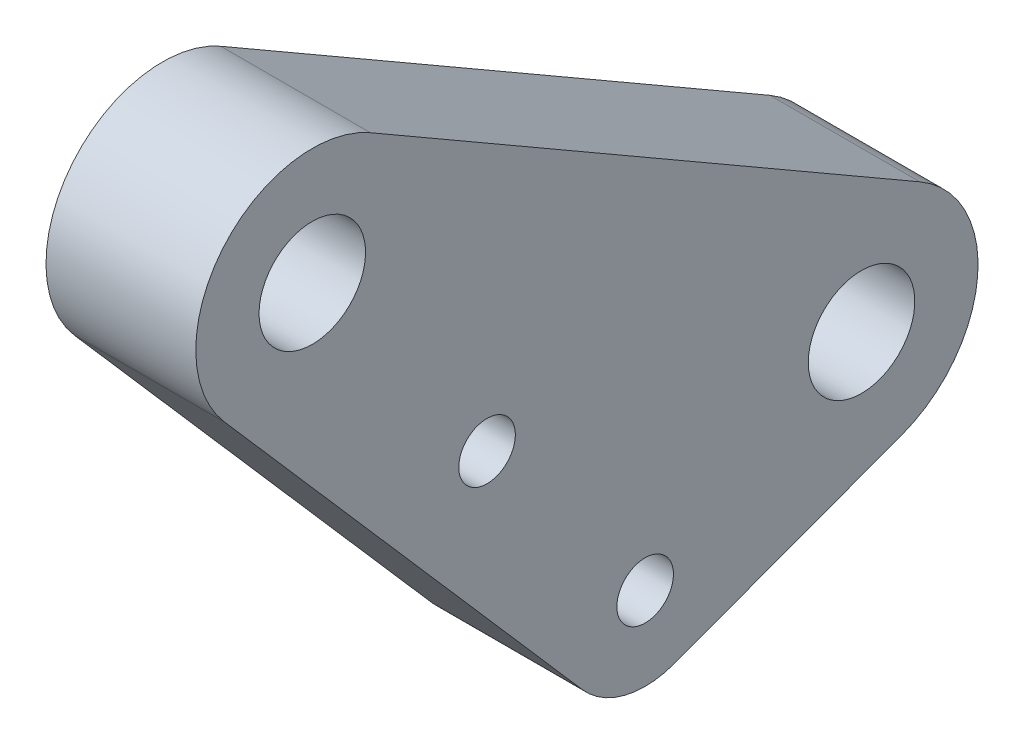
SolidWorks part; units mm, degrees
ref_plane "Front Plane" through (0, 0, 0) normal (0, 0, 1) x (1, 0, 0)
ref_plane "Top Plane" through (0, 0, 0) normal (0, 1, 0) x (1, 0, 0)
ref_plane "Right Plane" through (0, 0, 0) normal (1, 0, 0) x (0, 0, -1)
ref_plane "Plane4" through (9, 0, 0) normal (1, 0, 0) x (0, 0, -1)
sketch "Sketch1" plane through (9, 0, 0) normal (1, 0, 0) x (0, 0, -1)
  line L0 (3.5, 220.0622) -> (-29.5, 239.1147)
  line L1 (-38.2778, 228.4542) -> (-16.7699, 203.768)
  line L2 (-11.2635, 202.3638) -> (2.4311, 207.4357)
  circle A0 centre (-13, 207.0526) radius 1.7
  circle A1 centre (0, 214) radius 3.2
  circle A2 centre (-33, 233.0526) radius 3.2
  arc A3 (2.4311, 207.4357) -> (3.5, 220.0622) centre (0, 214) ccw
  arc A4 (-29.5, 239.1147) -> (-38.2778, 228.4542) centre (-33, 233.0526) ccw
  arc A5 (-16.7699, 203.768) -> (-11.2635, 202.3638) centre (-13, 207.0526) ccw
  circle A6 centre (-22.5, 219.0526) radius 1.7
extrude "Boss-Extrude1" add sketch "Sketch1" against normal blind 9
